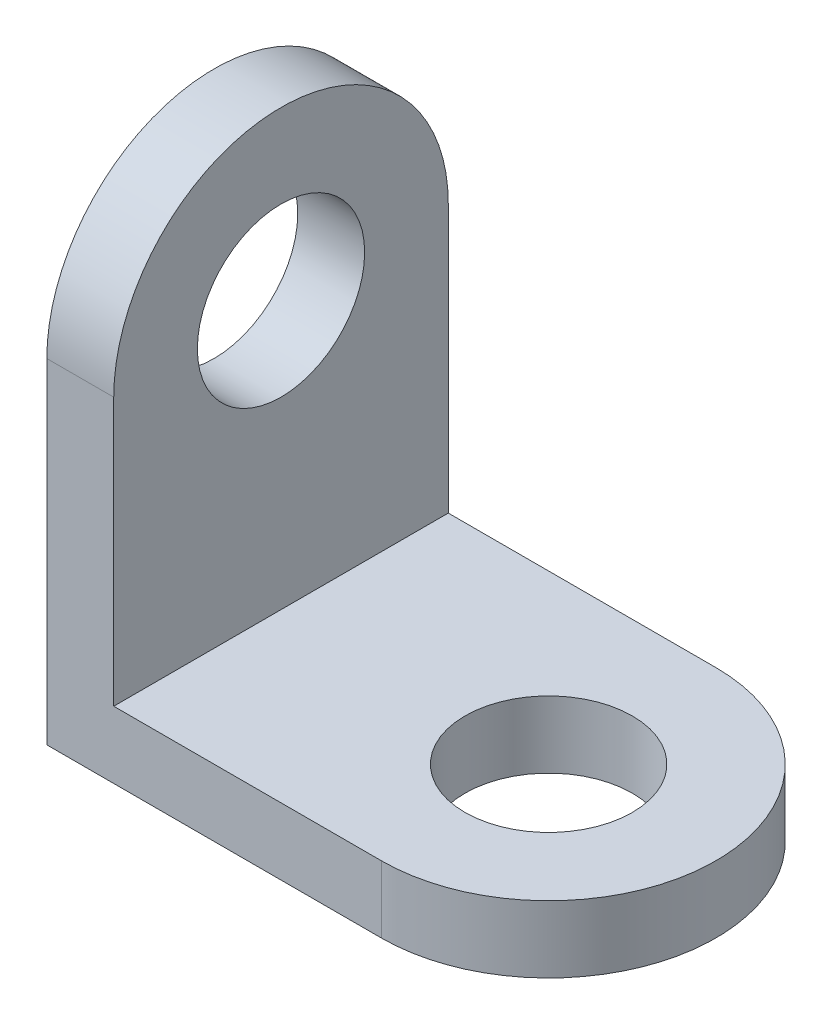
SolidWorks part; units mm, degrees
material "Zinco AC41A Liga, como fundido"
ref_plane "Plano frontal" through (0, 0, 0) normal (0, 0, 1) x (1, 0, 0)
ref_plane "Plano superior" through (0, 0, 0) normal (0, 1, 0) x (1, 0, 0)
ref_plane "Plano direito" through (0, 0, 0) normal (1, 0, 0) x (0, 0, -1)
sketch "Esboço1" plane through (0, 0, 0) normal (0, 1, 0) x (1, 0, 0)
  line L0 (0, 5) -> (-10, 5)
  line L1 (-10, 5) -> (-10, -5)
  line L2 (-10, -5) -> (0, -5)
  circle A0 centre (0, 0) radius 2.5
  circle A1 centre (0, 0) radius 5
  dimension "D1" = 5
  dimension "D2" = 10
  dimension "D3" = 10
extrude "Ressalto-extrusão1" add sketch "Esboço1" along normal blind 2 contours A1 L0 L1 L2 | A1 A0 | A0
sketch "Esboço2" plane through (-10, 0, 0) normal (-1, 0, 0) x (0, 0, 1)
  line L0 (5, 10) -> (5, 2)
  line L2 (5, 2) -> (-5, 2)
  line L3 (-5, 2) -> (-5, 10)
  circle A0 centre (0, 10) radius 2.5
  circle A1 centre (0, 10) radius 5
  dimension "D2" = 5
extrude "Ressalto-extrusão2" add sketch "Esboço2" against normal blind 2 contours A1 L3 L0 | A1 A0
